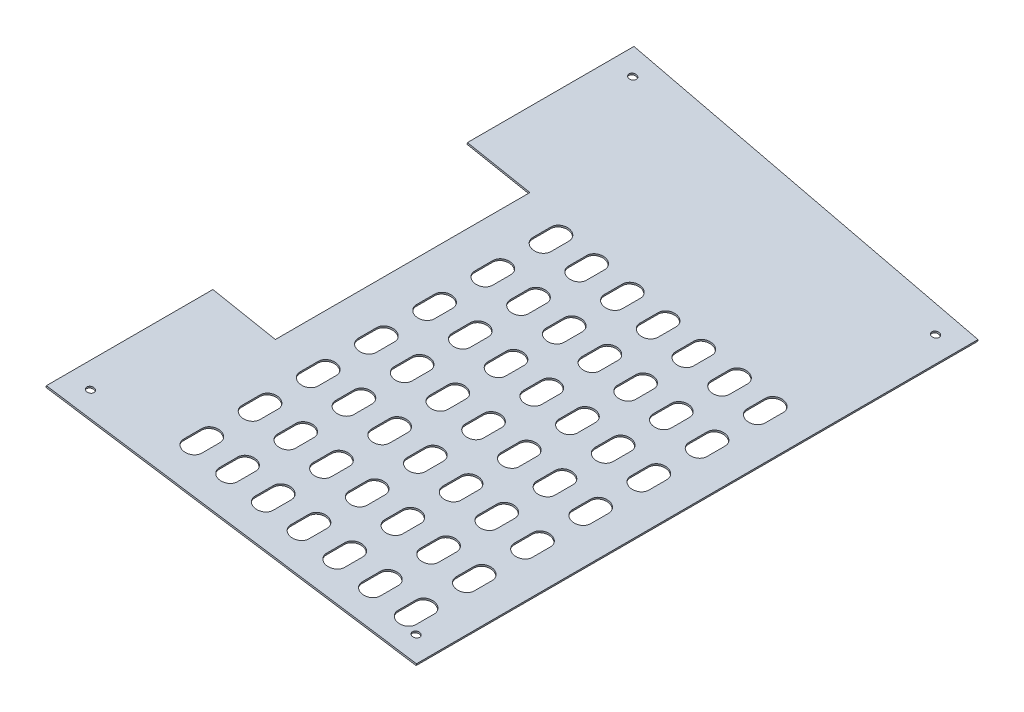
SolidWorks part; units mm, degrees
ref_plane "Front Plane" through (0, 0, 0) normal (0, 0, 1) x (1, 0, 0)
ref_plane "Top Plane" through (0, 0, 0) normal (0, 1, 0) x (1, 0, 0)
ref_plane "Right Plane" through (0, 0, 0) normal (1, 0, 0) x (0, 0, -1)
sketch3d "3DSketch1"
  line L3 (1335, 553.7618, -160.0082) -> (773.7071, 661.8641, -180.528)
  line L4 (1335, 553.7618, 160.0082) -> (773.7071, 661.8641, 180.528)
  line L5 (1007.5966, 616.8181, 171.9774) -> (1007.5966, 616.8181, -171.9774)
ref_plane "Plane1" through (150.5852, 781.8743, 0) normal (-0.1891, -0.982, 0) x (-0.982, 0.1891, 0)
sketch "Sketch2" plane through (150.5852, 781.8743, 0) normal (-0.1891, -0.982, 0) x (-0.982, 0.1891, 0)
  line L6 (-1205.5357, 142.0198) -> (-633.9276, 162.5396)
  line L7 (-860.7612, 154.3966) -> (-660.7612, 161.5763)
  line L9 (-1205.5357, -142.0198) -> (-633.9276, -162.5396)
  line L10 (-860.7612, -154.3966) -> (-660.7612, -161.5763)
  line L11 (-660.7612, -161.5763) -> (-660.7612, 161.5763)
  line L12 (-860.7612, -171.9774) -> (-860.7612, 171.9774)
  line L13 (-860.7612, -154.3966) -> (-860.7612, 154.3966)
  line L14 (-860.7612, -171.9774) -> (-860.7612, 171.9774) construction
  line L15 (-660.7612, -171.9774) -> (-660.7612, 171.9774) construction
  dimension "D1" = 18
  dimension "D2" = 18
  dimension "D3" = 12
  dimension "D4" = 200
extrude "Boss-Extrude1" add sketch "Sketch2" against normal blind 1 from offset 1.5
sketch "Sketch3" plane through (150.4907, 781.3834, 0) normal (0.1891, 0.982, 0) x (0.982, -0.1891, 0)
  line L0 (660.7612, -161.5763) -> (660.7612, 161.5763) construction
  line L1 (695.7612, -70) -> (625.7612, -70)
  line L2 (695.7612, -70) -> (695.7612, 70)
  line L3 (695.7612, 70) -> (625.7612, 70)
  line L4 (625.7612, -70) -> (625.7612, 70)
  line L5 (695.7612, -70) -> (625.7612, 70) construction
  line L6 (695.7612, 70) -> (625.7612, -70) construction
  point P0 (660.7612, 0)
  dimension "D1" = 70
  dimension "D2" = 140
extrude "Cut-Extrude1" cut sketch "Sketch3" against normal blind 10
sketch "Sketch4" plane through (150.4907, 781.3834, 0) normal (0.1891, 0.982, 0) x (0.982, -0.1891, 0)
  line L0 (672.7612, 149.1378) -> (848.7612, 142.8197) construction
  line L1 (660.7612, 161.5763) -> (860.7612, 154.3966) construction
  line L2 (860.7612, 154.3966) -> (860.7612, -154.3966) construction
  line L3 (660.7612, 70) -> (660.7612, 161.5763) construction
  circle A0 centre (672.7612, 149.1378) radius 2
  circle A1 centre (848.7612, 142.8197) radius 2
  dimension "D1" = 4
  dimension "D2" = 12
  dimension "D3" = 12
  dimension "D4" = 12
extrude "Cut-Extrude2" cut sketch "Sketch4" against normal blind 10
mirror "Mirror1" about plane through (0, 0, 0) normal (0, 0, 1) of "Cut-Extrude2"
sketch "Sketch5" plane through (150.4907, 781.3834, 0) normal (0.1891, 0.982, 0) x (0.982, -0.1891, 0)
  line L0 (839.6909, 63.0836) -> (839.6909, 53.0836) construction
  line L1 (844.6909, 63.0836) -> (844.6909, 53.0836)
  line L2 (834.6909, 63.0836) -> (834.6909, 53.0836)
  line L6 (839.6909, 53.0836) -> (704.6909, 53.0836) construction
  line L7 (839.6909, 53.0836) -> (839.6909, -126.9164) construction
  line L8 (839.6909, -126.9164) -> (704.6909, -126.9164) construction
  line L9 (704.6909, 53.0836) -> (704.6909, -126.9164) construction
  circle A0 centre (839.6909, 58.0836) radius 5 construction
  arc A4 (844.6909, 63.0836) -> (834.6909, 63.0836) centre (839.6909, 63.0836) ccw
  arc A5 (834.6909, 53.0836) -> (844.6909, 53.0836) centre (839.6909, 53.0836) ccw
  point P8 (839.6909, 58.0836)
  dimension "D2" = 135
  dimension "D3" = 10
  dimension "D1" = 180
  dimension "D4" = 10
extrude "Cut-Extrude3" cut sketch "Sketch5" against normal blind 10
pattern_linear "LPattern1" count 7 spacing 32 along (0, 0, 1) count 7 spacing 20 along (-0.982, 0.1891, 0) of "Cut-Extrude3"
